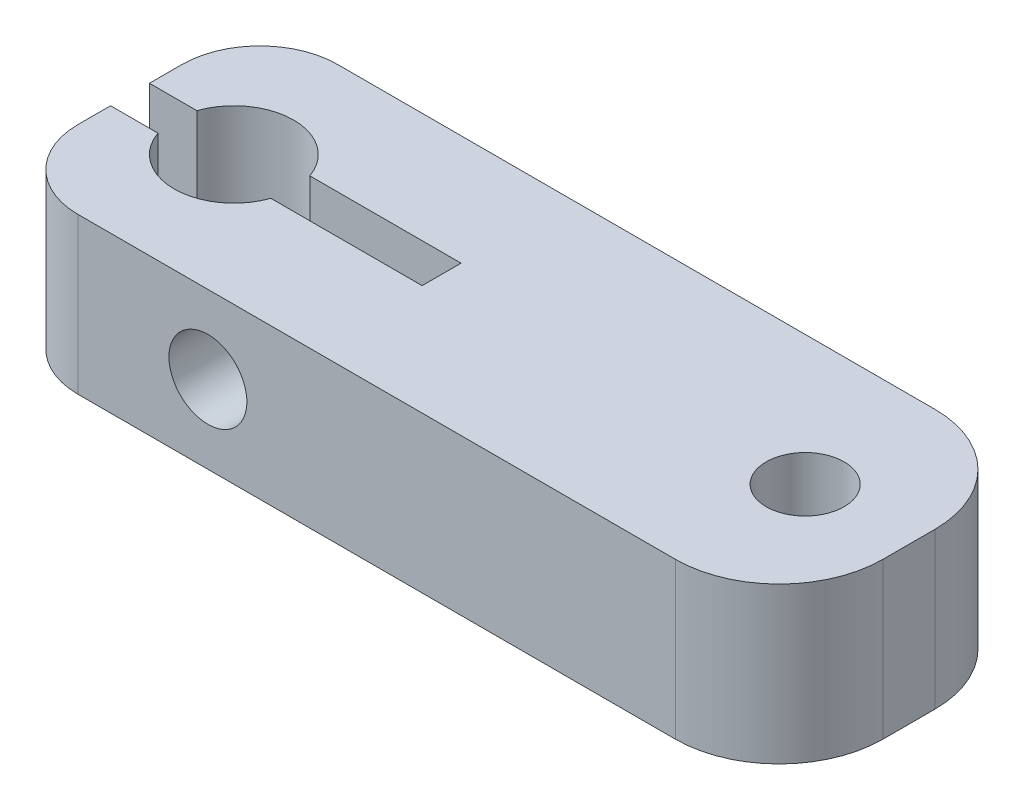
SolidWorks part; units mm, degrees
ref_plane "Front Plane" through (0, 0, 0) normal (0, 0, 1) x (1, 0, 0)
ref_plane "Top Plane" through (0, 0, 0) normal (0, 1, 0) x (1, 0, 0)
ref_plane "Right Plane" through (0, 0, 0) normal (1, 0, 0) x (0, 0, -1)
sketch "Sketch1" plane through (0, 0, 0) normal (0, 1, 0) x (1, 0, 0)
  line L1 (-12.0172, 17.3101) -> (17.9828, 17.3101)
  line L2 (-12.0172, 17.3101) -> (-12.0172, 7.3101)
  line L3 (-12.0172, 7.3101) -> (17.9828, 7.3101)
  line L4 (17.9828, 17.3101) -> (17.9828, 7.3101)
  circle A0 centre (-8.0172, 12.3101) radius 2.3
  circle A1 centre (13.9828, 12.3101) radius 1.5
  point P6 (17.9828, 12.3101)
  point P7 (-12.0172, 12.3101)
  dimension "D3" = 4.6
  dimension "D5" = 3
  dimension "D1" = 30
  dimension "D2" = 10
  dimension "D4" = 4
  dimension "D6" = 22
extrude "Boss-Extrude1" add sketch "Sketch1" along normal blind 6
fillet "Fillet1" radius 4 2 edges at (17.9828, 3, -17.3101) (17.9828, 3, -7.3101)
fillet "Fillet2" radius 3 2 edges at (-12.0172, 3, -7.3101) (-12.0172, 3, -17.3101)
sketch "Sketch3" plane through (0, 0, -17.3101) normal (0, 0, -1) x (-1, 0, 0)
  line L0 (9.0172, 0) -> (9.0172, 6) construction
  line L1 (12.0172, 6) -> (12.0172, 0) construction
  circle A0 centre (4.0172, 3) radius 1.5
  point P4 (9.0172, 3)
  dimension "D1" = 3
  dimension "D2" = 8
extrude "Cut-Extrude1" cut sketch "Sketch3" against normal up to next
sketch "Sketch4" plane through (0, 0, -17.3101) normal (0, 0, -1) x (-1, 0, 0)
  line L1 (-1.4293, 6) -> (-1.4293, 0)
  line L2 (-13.9828, 6) -> (9.0172, 6) construction
  line L3 (-13.9828, 0) -> (9.0172, 0) construction
  circle A0 centre (4.0172, 3) radius 1.75
  circle A5 centre (4.0172, 3) radius 1.5 construction
  point P11 (-1.4293, 3)
  dimension "D1" = 3.5
extrude "Cut-Extrude2" cut sketch "Sketch4" against normal blind 3 contours A0
sketch "Sketch7" plane through (0, 0, -17.3101) normal (0, 0, -1) x (-1, 0, 0)
  circle A0 centre (4.0172, 3) radius 2.5
  dimension "D1" = 5
extrude "Cut-Extrude6" cut sketch "Sketch7" against normal blind 3
sketch "Sketch8" plane through (0, 6, 0) normal (0, 1, 0) x (1, 0, 0)
  line L0 (13.9828, 17.3101) -> (-9.0172, 17.3101) construction
  line L1 (-12.0172, 13.0601) -> (-0.0172, 13.0601)
  line L2 (-12.0172, 13.0601) -> (-12.0172, 11.5601)
  line L3 (-12.0172, 11.5601) -> (-0.0172, 11.5601)
  line L4 (-0.0172, 13.0601) -> (-0.0172, 11.5601)
  line L5 (-12.0172, 14.3101) -> (-12.0172, 10.3101) construction
  dimension "D1" = 1.5
  dimension "D2" = 4.25
  dimension "D3" = 12
extrude "Cut-Extrude7" cut sketch "Sketch8" against normal up to next
